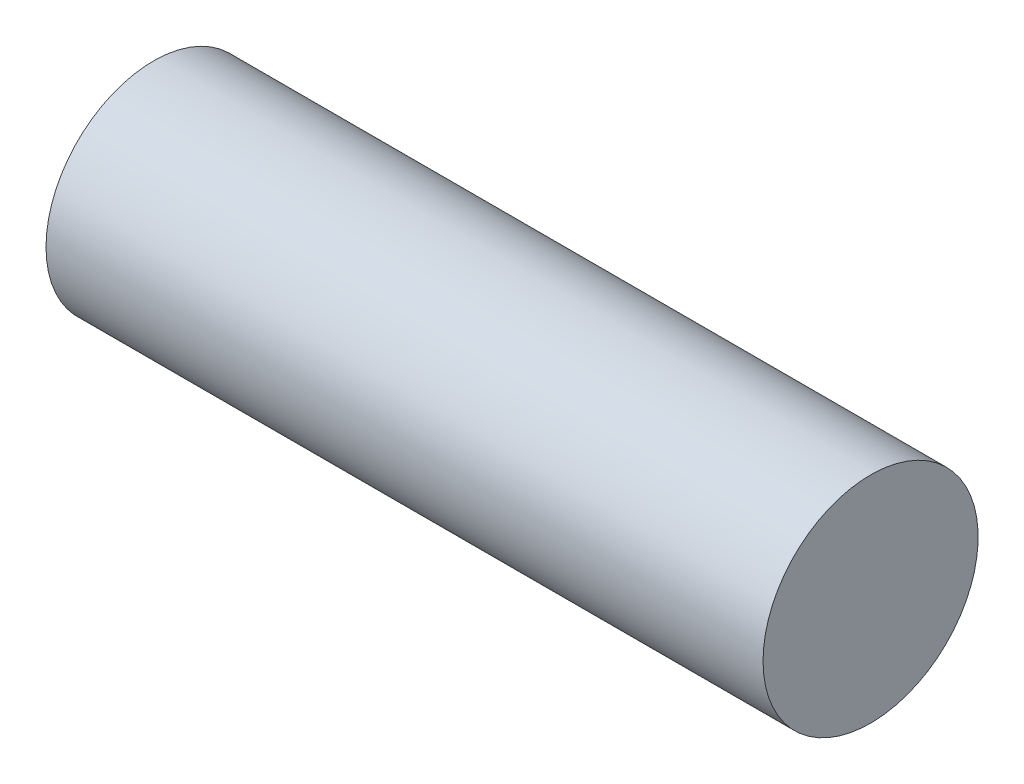
SolidWorks part; units mm, degrees
ref_plane "Ön Düzlem" through (0, 0, 0) normal (0, 0, 1) x (1, 0, 0)
ref_plane "Üst Düzlem" through (0, 0, 0) normal (0, 1, 0) x (1, 0, 0)
ref_plane "Sağ Düzlem" through (0, 0, 0) normal (1, 0, 0) x (0, 0, -1)
sketch "Sketch1" plane through (0, 0, 0) normal (0, 0, 1) x (1, 0, 0)
  line L1 (-55.9699, 6.1) -> (24.0301, 6.1)
  line L2 (-55.9699, 6.1) -> (-55.9699, -5.9)
  line L3 (-55.9699, -5.9) -> (24.0301, -5.9)
  line L4 (24.0301, 6.1) -> (24.0301, -5.9)
  dimension "D1" = 12
  dimension "D2" = 80
revolve "Revolve1" add sketch "Sketch1" angle 360 about L1
